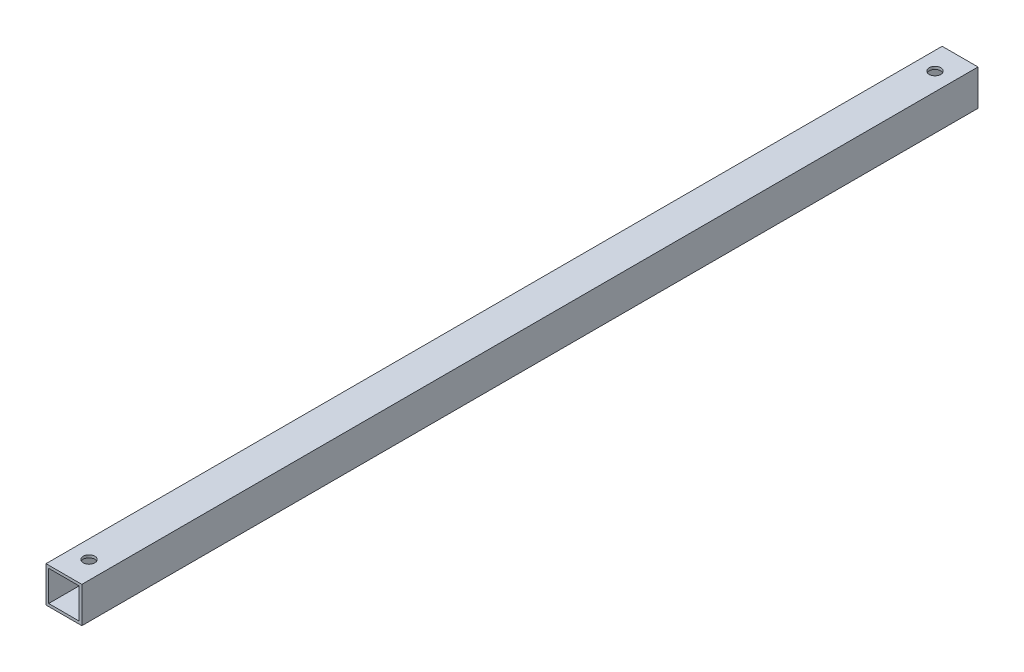
SolidWorks part; units mm, degrees
material "3.0205 (EN AW-1200)"
ref_plane "Ebene vorne" through (0, 0, 0) normal (0, 0, 1) x (1, 0, 0)
ref_plane "Ebene oben" through (0, 0, 0) normal (0, 1, 0) x (1, 0, 0)
ref_plane "Ebene rechts" through (0, 0, 0) normal (1, 0, 0) x (0, 0, -1)
sketch "Skizze1" plane through (0, 0, 0) normal (0, 0, 1) x (1, 0, 0)
  line L1 (10, -10) -> (-10, -10)
  line L2 (10, -10) -> (10, 10)
  line L3 (10, 10) -> (-10, 10)
  line L4 (-10, -10) -> (-10, 10)
  line L5 (10, -10) -> (-10, 10) construction
  line L6 (10, 10) -> (-10, -10) construction
  line L7 (8.5, -8.5) -> (-8.5, -8.5)
  line L8 (8.5, -8.5) -> (8.5, 8.5)
  line L9 (8.5, 8.5) -> (-8.5, 8.5)
  line L10 (-8.5, -8.5) -> (-8.5, 8.5)
  line L11 (8.5, -8.5) -> (-8.5, 8.5) construction
  line L12 (8.5, 8.5) -> (-8.5, -8.5) construction
  point P0 (0, 0)
  point P6 (0, 0)
  dimension "D1" = 20
  dimension "D2" = 1.5
extrude "Aufsatz-Linear austragen1" add sketch "Skizze1" against normal mid plane 500
sketch "Skizze2" plane through (0, 0, 0) normal (0, 1, 0) x (1, 0, 0)
  line L0 (0, -236) -> (0, 236) construction
  line L1 (10, -250) -> (-10, -250) construction
  circle A0 centre (0, -236) radius 3.25
  circle A1 centre (0, 236) radius 3.25
  dimension "D2" = 6.5
  dimension "D1" = 14
extrude "Schnitt-Linear austragen1" cut sketch "Skizze2" against normal mid plane 30
sketch "Skizze3" plane through (0, 0, 0) normal (1, 0, 0) x (0, 0, -1)
  line L0 (-240, 0) -> (240, 0) construction
  line L1 (-250, 10) -> (-250, -10) construction
  circle A0 centre (-240, 0) radius 3.25
  circle A1 centre (240, 0) radius 3.25
  point P2 (-250, 0)
  dimension "D2" = 6.5
  dimension "D3" = 6.5
  dimension "D1" = 10
extrude "Schnitt-Linear austragen2" [suppressed] cut sketch "Skizze3" against normal mid plane 30
sketch "Skizze4" [suppressed] plane through (0, 0, 0) normal (0, 1, 0) x (1, 0, 0)
  line L0 (0, -240) -> (0, 200) construction
  line L1 (-10, -250) -> (10, -250) construction
  line L2 (-10, 250) -> (10, 250) construction
  circle A0 centre (0, 200) radius 3.25
  circle A1 centre (0, -240) radius 3.25
  dimension "D3" = 6.5
  dimension "D1" = 10
  dimension "D2" = 50
extrude "Schnitt-Linear austragen3" [suppressed] cut sketch "Skizze4" against normal mid plane 50
